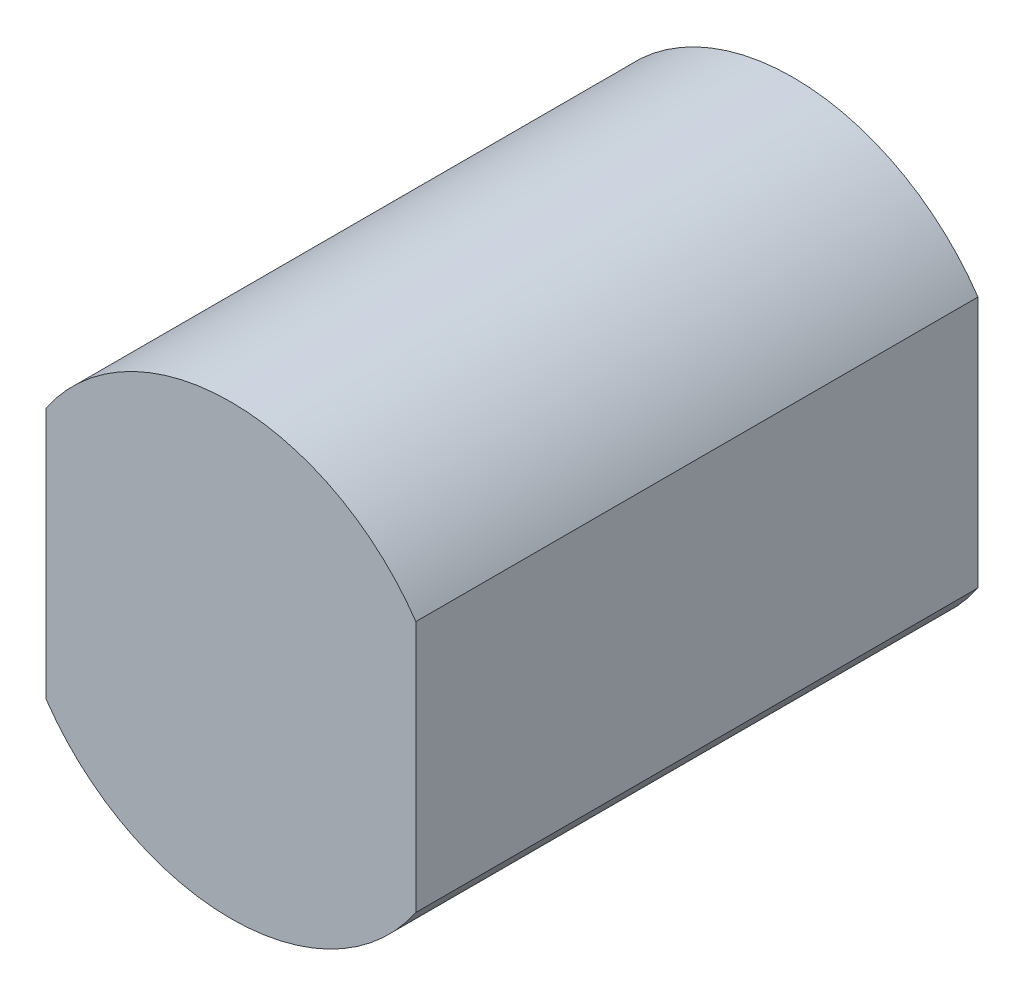
SolidWorks part; units mm, degrees
ref_plane "前视基准面" through (0, 0, 0) normal (0, 0, 1) x (1, 0, 0)
ref_plane "上视基准面" through (0, 0, 0) normal (0, 1, 0) x (1, 0, 0)
ref_plane "右视基准面" through (0, 0, 0) normal (1, 0, 0) x (0, 0, -1)
sketch "草图1" plane through (0, 0, 0) normal (0, 0, 1) x (1, 0, 0)
  line L2 (-5, -3.4062) -> (-5, 3.4062)
  line L4 (5, -3.4062) -> (5, 3.4062)
  line L5 (-5, -6.05) -> (5, 6.05) construction
  line L6 (-3.8541, 4.6635) -> (5, -6.05) construction
  arc A0 (-5, -3.4062) -> (5, -3.4062) centre (0, 0) ccw
  arc A1 (5, 3.4062) -> (-5, 3.4062) centre (0, 0) ccw
  point P0 (0, 0)
extrude "凸台-拉伸1" add sketch "草图1" along normal blind 15.2
